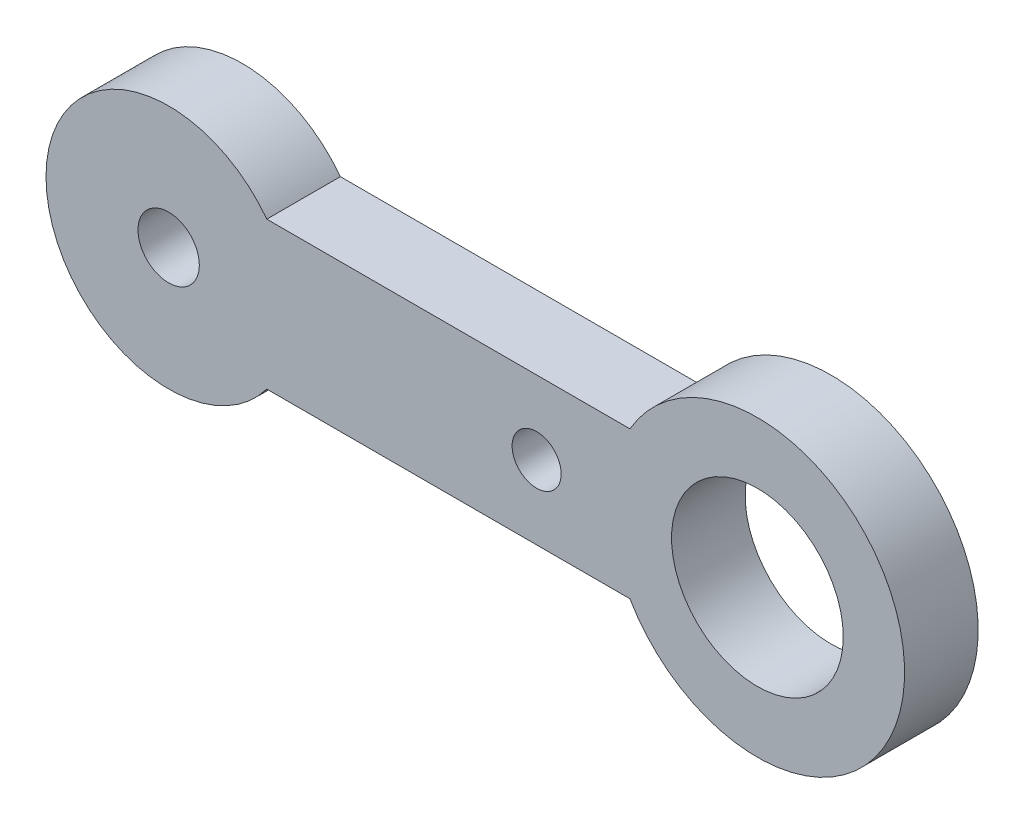
SolidWorks part; units mm, degrees
ref_plane "Front Plane" through (0, 0, 0) normal (0, 0, 1) x (1, 0, 0)
ref_plane "Top Plane" through (0, 0, 0) normal (0, 1, 0) x (1, 0, 0)
ref_plane "Right Plane" through (0, 0, 0) normal (1, 0, 0) x (0, 0, -1)
sketch "Sketch2" plane through (0, 0, 0) normal (0, 0, 1) x (1, 0, 0)
  line L0 (-1.3062, 0) -> (22.6938, 0) construction
  line L1 (2.6938, 3) -> (17.4976, 3)
  line L2 (2.6938, -3) -> (17.4976, -3)
  circle A0 centre (-1.3062, 0) radius 1.25
  circle A1 centre (22.6938, 0) radius 3.5
  arc A2 (2.6938, 3) -> (2.6938, -3) centre (-1.3062, 0) ccw
  arc A3 (17.4976, -3) -> (17.4976, 3) centre (22.6938, 0) ccw
  circle A4 centre (13.6938, 0) radius 1
  dimension "D2" = 2.5
  dimension "D3" = 7
  dimension "D4" = 10
  dimension "D5" = 12
  dimension "D8" = 9
  dimension "D9" = 2
  dimension "D1" = 24
  dimension "D6" = 3
  dimension "D7" = 3
extrude "Boss-Extrude1" add sketch "Sketch2" along normal blind 3
